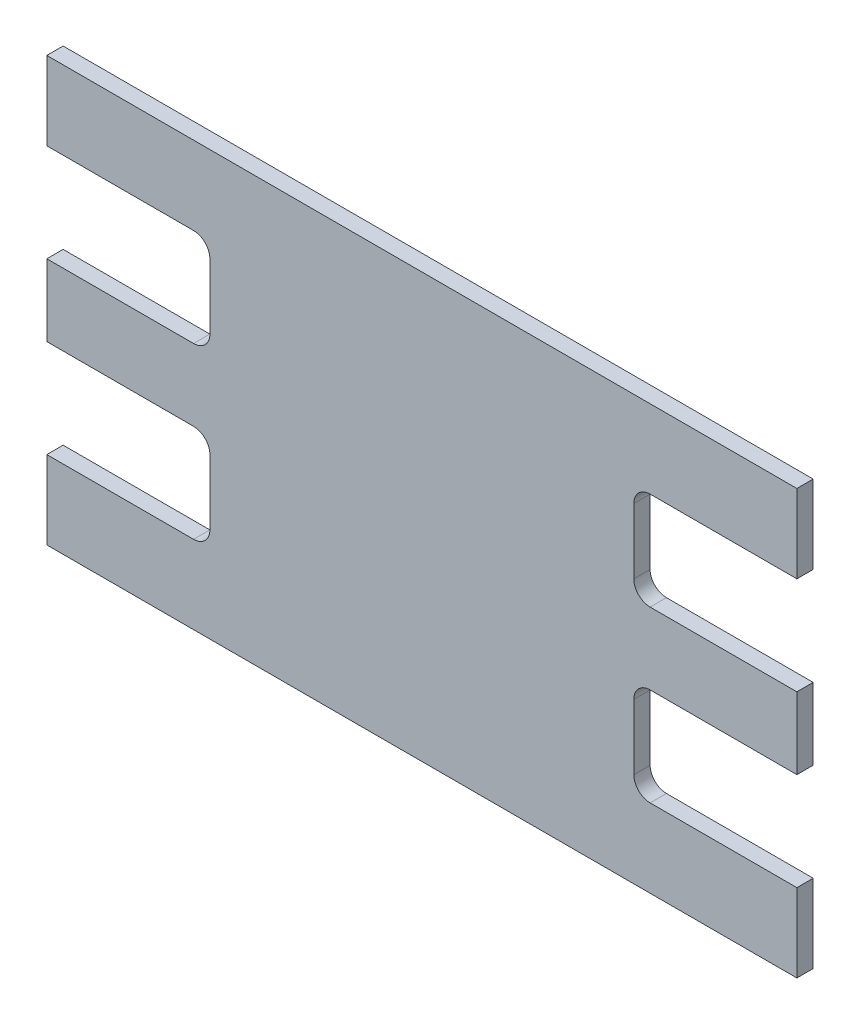
SolidWorks part; units mm, degrees
material "ABS PC"
ref_plane "Front Plane" through (0, 0, 0) normal (0, 0, 1) x (1, 0, 0)
ref_plane "Top Plane" through (0, 0, 0) normal (0, 1, 0) x (1, 0, 0)
ref_plane "Right Plane" through (0, 0, 0) normal (1, 0, 0) x (0, 0, -1)
sketch "Sketch1" plane through (0, 0, 0) normal (0, 0, 1) x (1, 0, 0)
  line L1 (-146.05, 82.55) -> (146.05, 82.55)
  line L2 (-146.05, 82.55) -> (-146.05, -82.55)
  line L3 (-146.05, -82.55) -> (146.05, -82.55)
  line L4 (146.05, 82.55) -> (146.05, -82.55)
  line L5 (-146.05, 82.55) -> (146.05, -82.55) construction
  line L6 (-146.05, -82.55) -> (146.05, 82.55) construction
  point P0 (0, 0)
  dimension "D1" = 292.1
  dimension "D2" = 165.1
extrude "Boss-Extrude1" add sketch "Sketch1" along normal blind 6.35
sketch "Sketch2" plane through (0, 0, 6.35) normal (0, 0, 1) x (1, 0, 0)
  line L0 (-146.05, 52.07) -> (-88.9, 52.07)
  line L1 (-146.05, 82.55) -> (-146.05, -82.55) construction
  line L2 (-82.55, 45.72) -> (-82.55, 20.32)
  line L3 (-88.9, 13.97) -> (-146.05, 13.97)
  line L4 (-146.05, 13.97) -> (-146.05, 52.07)
  line L5 (146.05, 82.55) -> (-146.05, 82.55) construction
  line L6 (-180.5555, 0) -> (156.9456, 0) construction
  line L7 (0, 100.7963) -> (0, -101.099) construction
  line L8 (-146.05, -13.97) -> (-146.05, -52.07)
  line L9 (-88.9, -13.97) -> (-146.05, -13.97)
  line L10 (-82.55, -45.72) -> (-82.55, -20.32)
  line L11 (-146.05, -52.07) -> (-88.9, -52.07)
  line L12 (146.05, -52.07) -> (88.9, -52.07)
  line L13 (82.55, -45.72) -> (82.55, -20.32)
  line L14 (88.9, -13.97) -> (146.05, -13.97)
  line L15 (146.05, -13.97) -> (146.05, -52.07)
  line L16 (146.05, 13.97) -> (146.05, 52.07)
  line L17 (88.9, 13.97) -> (146.05, 13.97)
  line L18 (82.55, 45.72) -> (82.55, 20.32)
  line L19 (146.05, 52.07) -> (88.9, 52.07)
  arc A0 (-88.9, 13.97) -> (-82.55, 20.32) centre (-88.9, 20.32) ccw
  arc A1 (-82.55, 45.72) -> (-88.9, 52.07) centre (-88.9, 45.72) ccw
  arc A2 (-82.55, -45.72) -> (-88.9, -52.07) centre (-88.9, -45.72) cw
  arc A3 (-88.9, -13.97) -> (-82.55, -20.32) centre (-88.9, -20.32) cw
  arc A4 (88.9, -13.97) -> (82.55, -20.32) centre (88.9, -20.32) ccw
  arc A5 (82.55, -45.72) -> (88.9, -52.07) centre (88.9, -45.72) ccw
  arc A6 (82.55, 45.72) -> (88.9, 52.07) centre (88.9, 45.72) cw
  arc A7 (88.9, 13.97) -> (82.55, 20.32) centre (88.9, 20.32) cw
  point P21 (-82.55, -52.07)
  point P22 (-82.55, -13.97)
  point P27 (-82.55, 13.97)
  point P30 (-82.55, 52.07)
  point P45 (82.55, 52.07)
  point P46 (82.55, 13.97)
  point P47 (82.55, -13.97)
  point P48 (82.55, -52.07)
  dimension "D4" = 6.35
  dimension "D1" = 63.5
  dimension "D2" = 38.1
  dimension "D3" = 30.48
extrude "Cut-Extrude1" cut sketch "Sketch2" against normal through all
